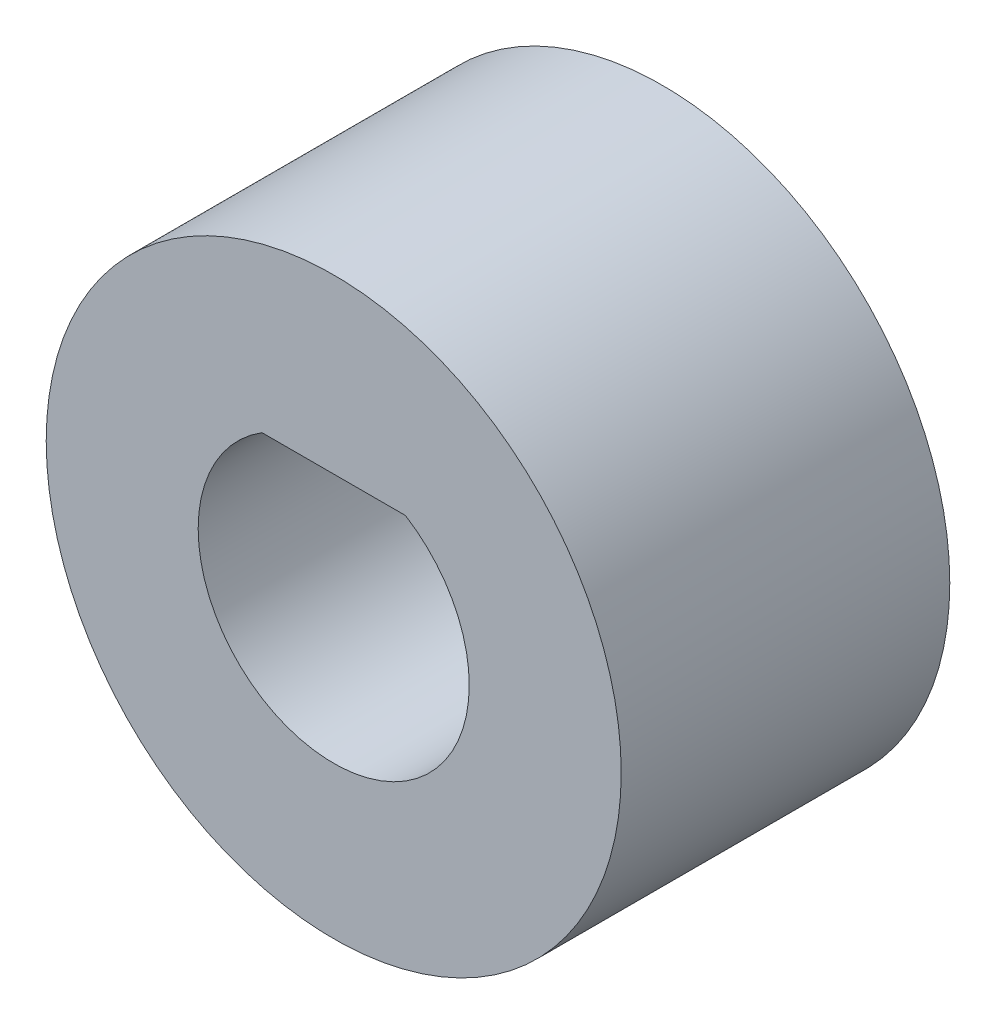
SolidWorks part; units mm, degrees
ref_plane "Plan de face" through (0, 0, 0) normal (0, 0, 1) x (1, 0, 0)
ref_plane "Plan de dessus" through (0, 0, 0) normal (0, 1, 0) x (1, 0, 0)
ref_plane "Plan de droite" through (0, 0, 0) normal (1, 0, 0) x (0, 0, -1)
sketch "Esquisse1" plane through (0, 0, 0) normal (0, 0, 1) x (1, 0, 0)
  line L0 (-1.7464, 2.8) -> (1.7464, 2.8)
  line L1 (-0.9885, -3.3) -> (1.037, -3.3) construction
  circle A0 centre (0, 0) radius 7
  arc A1 (-1.7464, 2.8) -> (1.7464, 2.8) centre (0, 0) ccw
  dimension "D1" = 14
  dimension "D2" = 6.6
  dimension "D3" = 6.1
extrude "Boss.-Extru.1" add sketch "Esquisse1" along normal blind 8
